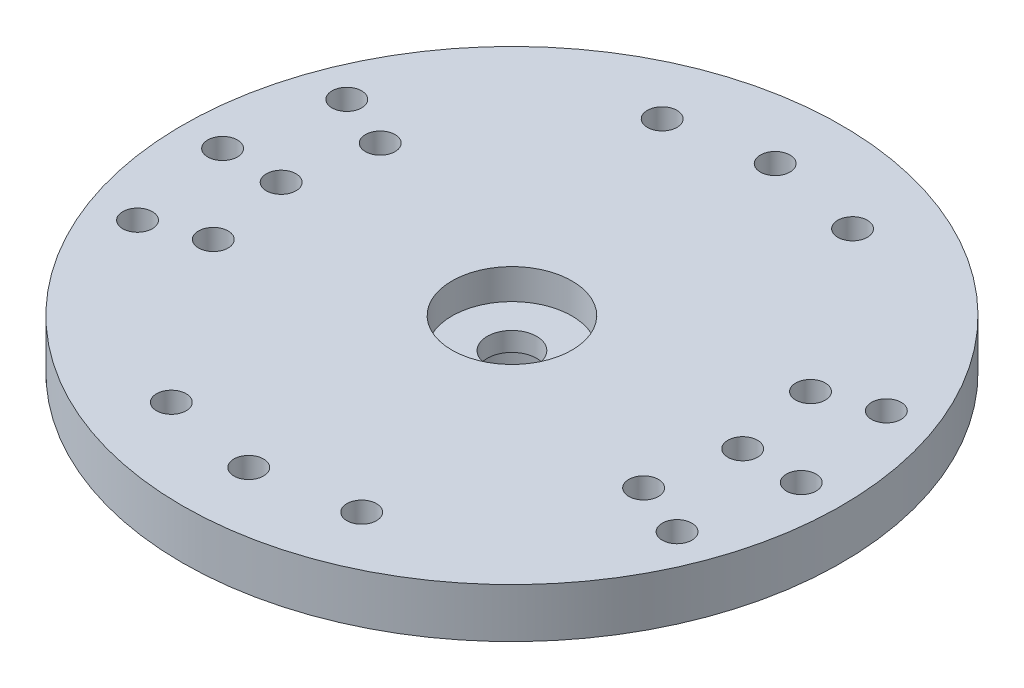
SolidWorks part; units mm, degrees
ref_plane "Front Plane" through (0, 0, 0) normal (0, 0, 1) x (1, 0, 0)
ref_plane "Top Plane" through (0, 0, 0) normal (0, 1, 0) x (1, 0, 0)
ref_plane "Right Plane" through (0, 0, 0) normal (1, 0, 0) x (0, 0, -1)
sketch "Sketch1" plane through (0, 0, 0) normal (0, 1, 0) x (1, 0, 0)
  circle A0 centre (0, 0) radius 11.8618
  circle A1 centre (0, 0) radius 0.889
  dimension "D1" = 23.7236
  dimension "D2" = 1.778
extrude "Boss-Extrude1" add sketch "Sketch1" along normal blind 1.778
sketch "Sketch2" plane through (0, 0, 0) normal (0, -1, 0) x (1, 0, 0)
  circle A0 centre (0, 0) radius 3.4417
  circle A1 centre (0, 0) radius 2.1907
  dimension "D1" = 6.8834
  dimension "D2" = 4.3815
extrude "Boss-Extrude2" add sketch "Sketch2" along normal blind 3.048
sketch "Sketch3" plane through (0, 1.778, 0) normal (0, 1, 0) x (1, 0, 0)
  circle A0 centre (0, 0) radius 2.159
  circle M2 centre (0, 0) radius 0.889
  dimension "D1" = 4.318
extrude "Cut-Extrude1" cut sketch "Sketch3" against normal blind 1.0922 contours A0 M2
sketch "Sketch4" plane through (0, 1.778, 0) normal (0, 1, 0) x (1, 0, 0)
  line L0 (0, 0) -> (0, 50000) construction
  line L1 (0, 0) -> (50000, 0) construction
  line L2 (0, 0) -> (-18079.5218, 46616.852) construction
  line L3 (0, 0) -> (18079.5218, 46616.852) construction
  line L4 (0, 0) -> (46616.1901, 18081.2285) construction
  line L5 (0, 0) -> (46616.1901, -18081.2285) construction
  circle A0 centre (0, 9.4742) radius 0.5334
  circle A1 centre (10.414, 0) radius 0.5334
  circle A2 centre (8.3058, 0) radius 0.5334
  circle A3 centre (3.4258, 8.8331) radius 0.5334
  circle A4 centre (-3.4258, 8.8331) radius 0.5334
  circle A5 centre (0, 0) radius 9.4742
  circle A6 centre (0, 0) radius 10.414
  circle A7 centre (0, 0) radius 8.3058
  circle A8 centre (0, 0) radius 11.8618 construction
  circle A9 centre (7.7437, 3.0036) radius 0.5334
  circle A10 centre (9.7092, 3.766) radius 0.5334
  circle A11 centre (7.7437, -3.0036) radius 0.5334
  circle A12 centre (9.7092, -3.766) radius 0.5334
  circle A13 centre (3.4258, -8.8331) radius 0.5334
  circle A14 centre (0, -9.4742) radius 0.5334
  circle A15 centre (-3.4258, -8.8331) radius 0.5334
  circle A16 centre (-9.7092, -3.766) radius 0.5334
  circle A17 centre (-7.7437, -3.0036) radius 0.5334
  circle A18 centre (-9.7092, 3.766) radius 0.5334
  circle A19 centre (-7.7437, 3.0036) radius 0.5334
  circle A20 centre (-8.3058, 0) radius 0.5334
  circle A21 centre (-10.414, 0) radius 0.5334
  dimension "D1" = 1.0668
  dimension "D2" = 1.4478
  dimension "D3" = 2.3876
  dimension "D4" = 3.556
  dimension "D6" = 3.5052
  dimension "D7" = 21.2
  dimension "D8" = 21.2
  dimension "D9" = 3.5052
  dimension "D10" = 3.5052
extrude "Cut-Extrude2" cut sketch "Sketch4" against normal through all contours A21 | A16 | A17 | A20 | A19 | A18 | A4 | A0 | A3 | A9 | A10 | A1 | A2 | A11 | A12 | A15 | A14 | A13
